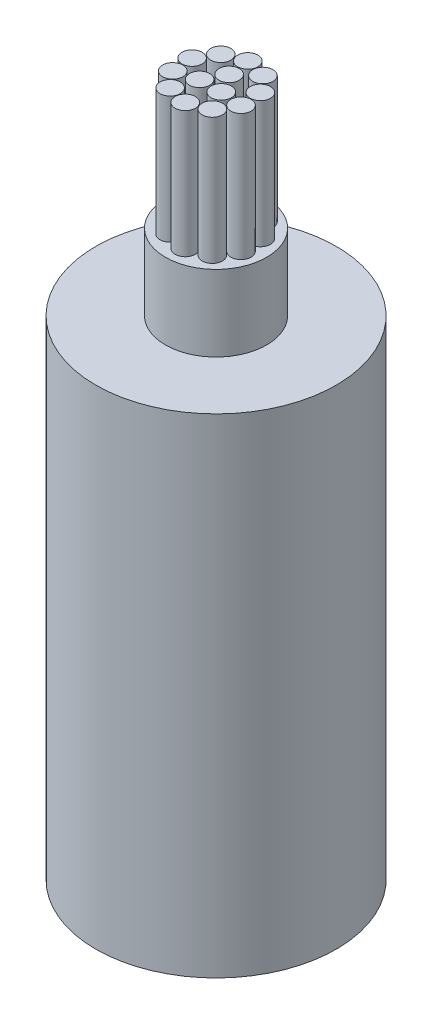
SolidWorks part; units mm, degrees
ref_plane "Front Plane" through (0, 0, 0) normal (0, 0, 1) x (1, 0, 0)
ref_plane "Top Plane" through (0, 0, 0) normal (0, 1, 0) x (1, 0, 0)
ref_plane "Right Plane" through (0, 0, 0) normal (1, 0, 0) x (0, 0, -1)
sketch "Sketch1" plane through (0, 0, 0) normal (0, 1, 0) x (1, 0, 0)
  circle A0 centre (0, 0) radius 6.2
  dimension "D1" = 12.4
extrude "Boss-Extrude1" add sketch "Sketch1" along normal blind 19.5
sketch "Sketch2" plane through (0, 19.5, 0) normal (0, 1, 0) x (1, 0, 0)
  circle A0 centre (0, 0) radius 2
  dimension "D1" = 4
extrude "Boss-Extrude2" add sketch "Sketch2" along normal blind 2.8
sketch "Sketch3" plane through (0, 22.3, 0) normal (0, 1, 0) x (1, 0, 0)
  circle A0 centre (-0.4115, -0.2373) radius 0.4
  circle A1 centre (-0.0913, 1.3462) radius 0.4
  circle A2 centre (0.7061, 1.1465) radius 0.4
  circle A3 centre (1.2337, 0.5162) radius 0.4
  circle A4 centre (1.2901, -0.3038) radius 0.4
  circle A5 centre (0.8538, -1.0004) radius 0.4
  circle A6 centre (0.0913, -1.3075) radius 0.4
  circle A7 centre (-0.7061, -1.1078) radius 0.4
  circle A8 centre (-1.2337, -0.4775) radius 0.4
  circle A9 centre (-1.2901, 0.3426) radius 0.4
  circle A10 centre (-0.8538, 1.0392) radius 0.4
  circle A11 centre (0, 0.5162) radius 0.4
  circle A12 centre (0.4417, -0.2373) radius 0.4
  point P25 (0, 0.0194)
  dimension "D1" = 0.8
  dimension "D3" = 10
extrude "Boss-Extrude4" add sketch "Sketch3" along normal blind 5
sketch "Sketch4" plane through (0, 19.5, 0) normal (0, 1, 0) x (1, 0, 0)
  circle A0 centre (0, 0) radius 4.75
  circle A1 centre (0, 0) radius 2 construction
  circle A2 centre (0, 0) radius 2
  dimension "D1" = 9.5
extrude "Cut-Extrude1" cut sketch "Sketch4" against normal blind 0.2
sketch "Sketch5" plane through (0, 0, 0) normal (0, -1, 0) x (1, 0, 0)
  line L0 (-1.52, 0) -> (1.4539, 0) construction
  line L1 (0, 1.5944) -> (0, -1.4457) construction
  circle A0 centre (-5.7001, 0) radius 0.4
  circle A1 centre (-5.6299, 0.8917) radius 0.4
  circle A2 centre (-4.7914, 0) radius 0.4
  circle A3 centre (-4.7034, 0.9142) radius 0.4
  circle A4 centre (-4.7034, -0.9142) radius 0.4
  circle A5 centre (-5.6299, -0.8917) radius 0.4
  circle A6 centre (5.6299, -0.8917) radius 0.4
  circle A7 centre (4.7034, -0.9142) radius 0.4
  circle A8 centre (4.7034, 0.9142) radius 0.4
  circle A9 centre (4.7914, 0) radius 0.4
  circle A10 centre (5.6299, 0.8917) radius 0.4
  circle A11 centre (5.7001, 0) radius 0.4
  point P6 (0, 0)
  point P12 (0, 0)
  dimension "D1" = 0.8
  dimension "D2" = 2
  dimension "D3" = 2
extrude "Boss-Extrude5" add sketch "Sketch5" along normal blind 3.5
sketch "Sketch6" plane through (0, 19.5, 0) normal (0, 1, 0) x (1, 0, 0)
  circle A0 centre (0, 0) radius 4.75 construction
  circle A1 centre (0, 0) radius 6.2
  circle A2 centre (0, 0) radius 6.2
  circle A3 centre (0, 0) radius 4.75
  dimension "D1" = 0
extrude "Cut-Extrude2" cut sketch "Sketch6" against normal through all
sketch "Sketch7" plane through (0, 0, 0) normal (0, -1, 0) x (1, 0, 0)
  circle A0 centre (0, 0) radius 9.5127
extrude "Cut-Extrude3" cut sketch "Sketch7" along normal through all
